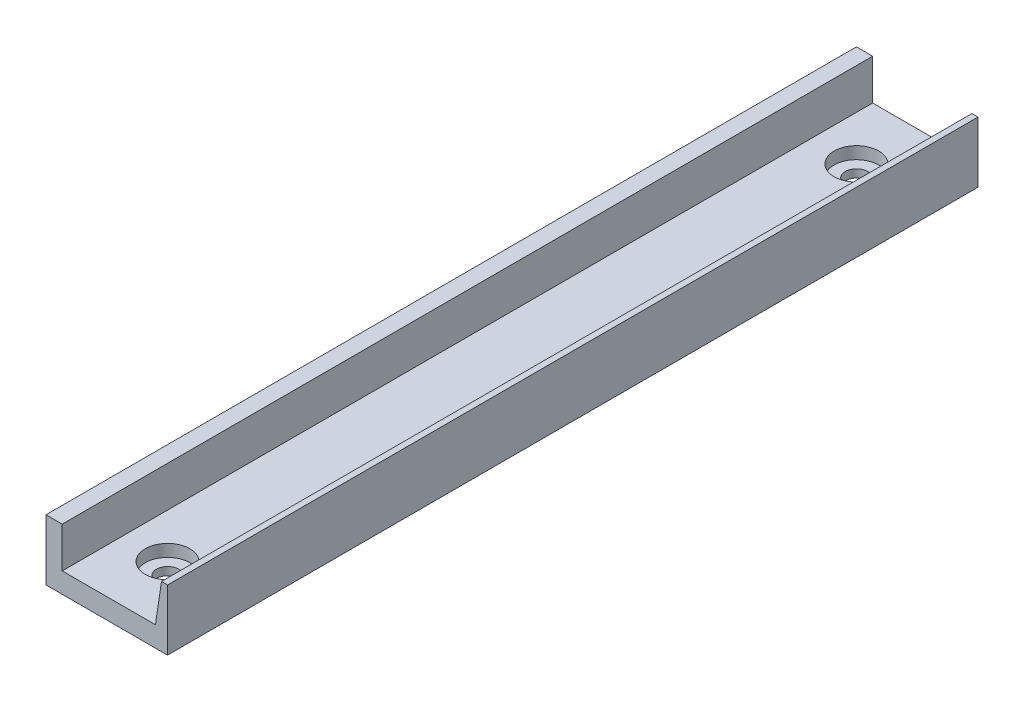
SolidWorks part; units mm, degrees
material "PLA"
ref_plane "정면" through (0, 0, 0) normal (0, 0, 1) x (1, 0, 0)
ref_plane "윗면" through (0, 0, 0) normal (0, 1, 0) x (1, 0, 0)
ref_plane "우측면" through (0, 0, 0) normal (1, 0, 0) x (0, 0, -1)
sketch "스케치1" plane through (0, 0, 0) normal (0, 1, 0) x (1, 0, 0)
  line L1 (-15, 100) -> (15, 100)
  line L2 (-15, 100) -> (-15, -100)
  line L3 (-15, -100) -> (15, -100)
  line L4 (15, 100) -> (15, -100)
  line L5 (-15, 100) -> (15, -100) construction
  line L6 (-15, -100) -> (15, 100) construction
  point P0 (0, 0)
  dimension "D1" = 200
  dimension "D2" = 30
extrude "보스-돌출1" add sketch "스케치1" along normal blind 5
sketch "스케치2" plane through (0, 5, 0) normal (0, 1, 0) x (1, 0, 0)
  line L0 (-15, -100) -> (15, -100) construction
  line L1 (-15, 100) -> (-11, 100)
  line L2 (-15, 100) -> (-15, -100)
  line L3 (-15, -100) -> (-11, -100)
  line L4 (-11, 100) -> (-11, -100)
  line L6 (15, 100) -> (12, 100)
  line L7 (15, 100) -> (15, -100)
  line L8 (15, -100) -> (12, -100)
  line L9 (12, 100) -> (12, -100)
  dimension "D1" = 4
  dimension "D2" = 3
extrude "보스-돌출2" add sketch "스케치2" along normal blind 10
sketch "스케치3" plane through (0, 0, 100) normal (0, 0, 1) x (1, 0, 0)
  line L19 (12, 5) -> (12, 15)
  line L24 (13.5, 15) -> (12, 5)
  line L25 (12, 15) -> (15, 15) construction
  line L26 (12, 15) -> (13.5, 15)
extrude "컷-돌출1" cut sketch "스케치3" against normal through all
hole_wizard "M5 소켓 머리 캡 나사용 카운터보어1" positions "스케치5" profile "스케치6" counterbore size "M5" standard "KS"
sketch "스케치5" plane through (0, 5, 0) normal (0, 1, 0) x (1, 0, 0)
  line L0 (-11, -100) -> (12, -100) construction
  line L1 (12, 100) -> (-11, 100) construction
  line L3 (-15, 100) -> (-15, -100) construction
  point P0 (0, -85)
  point P2 (0, 85)
  point P15 (0, -85)
  dimension "D1" = 15
  dimension "D2" = 15
  dimension "D3" = 15
  dimension "D4" = 15
sketch "스케치6" plane through (0, 5, 85) normal (1, 0, 0) x (0, 0, 1)
  line L0 (0, 0) -> (0, 31.6524)
  line L1 (0, 31.6524) -> (2.75, 30)
  line L2 (2.75, 30) -> (2.75, 3)
  line L3 (2.75, 3) -> (5.5, 3)
  line L4 (5.5, 3) -> (5.5, 0)
  line L5 (5.5, 0) -> (0, 0)
  line L10 (0, 31.6524) -> (-2.75, 30) construction
  line L11 (0, -6.35) -> (0, 107.95) construction
  dimension "구멍 지름" = 5.5
  dimension "구멍 깊이" = 30
  dimension "카운터보어 지름" = 11
  dimension "카운터보어 깊이" = 3
  dimension "드릴 각도" = 118
sketch "스케치7" plane through (0, 0, 0) normal (0, -1, 0) x (1, 0, 0)
  line L1 (-3.05, 60) -> (3.05, 60)
  line L2 (-3.05, 60) -> (-3.05, -60)
  line L3 (-3.05, -60) -> (3.05, -60)
  line L4 (3.05, 60) -> (3.05, -60)
  line L5 (-3.05, 60) -> (3.05, -60) construction
  line L6 (-3.05, -60) -> (3.05, 60) construction
  point P0 (0, 0)
  dimension "D1" = 6.1
  dimension "D2" = 120
extrude "보스-돌출3" add sketch "스케치7" along normal blind 6
